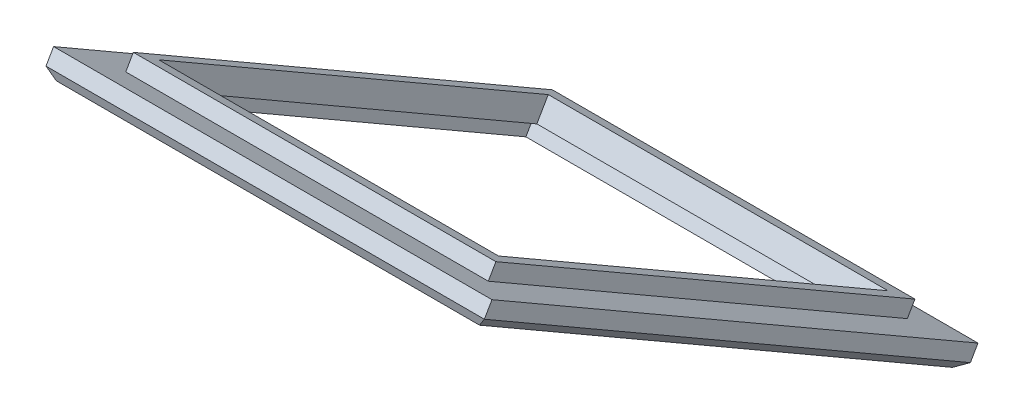
SolidWorks part; units mm, degrees
ref_plane "Front Plane" through (0, 0, 0) normal (1, 0, 0) x (0, 1, 0)
ref_plane "Top Plane" through (0, 0, 0) normal (0, 0, 1) x (0, 1, 0)
ref_plane "Right Plane" through (0, 0, 0) normal (0, 1, 0) x (-1, 0, 0)
sketch "Sketch1" plane through (0, -73.8743, 42.6513) normal (0, -0.866, 0.5) x (1, 0, 0)
  line L0 (-20.3754, 34.8073) -> (24.4246, 34.8073) construction
  line L1 (24.4246, 34.8073) -> (24.4246, 94.1073) construction
  line L2 (24.4246, 94.1073) -> (-20.3754, 94.1073) construction
  line L3 (-20.3754, 94.1073) -> (-20.3754, 34.8073) construction
  line L16 (-20.3754, 34.8073) -> (24.4246, 34.8073)
  line L17 (24.4246, 34.8073) -> (24.4246, 94.1073)
  line L18 (24.4246, 94.1073) -> (-20.3754, 94.1073)
  line L19 (-20.3754, 94.1073) -> (-20.3754, 34.8073)
  line L20 (-26.8754, 27.4573) -> (30.9246, 27.4573)
  line L21 (30.9246, 27.4573) -> (30.9246, 101.4573)
  line L22 (30.9246, 101.4573) -> (-26.8754, 101.4573)
  line L23 (-26.8754, 101.4573) -> (-26.8754, 27.4573)
  dimension "D1" = 6.5
  dimension "D2" = 7.35
  dimension "D3" = 7.35
  dimension "D4" = 6.5
extrude "Boss-Extrude1" add sketch "Sketch1" against normal blind 3
chamfer "Chamfer1" distance 1 angle 45 8 edges at (2.0246, -56.4706, 72.7953) (24.4246, -41.6456, 98.473) (2.0246, -26.8206, 124.1506) (-20.3754, -41.6456, 98.473) (2.0246, -60.1456, 66.4301) (30.9246, -41.6456, 98.473) (-26.8754, -41.6456, 98.473) (2.0246, -23.1456, 130.5159)
sketch "Sketch2" plane through (0, -71.2762, 41.1513) normal (0, 0.866, -0.5) x (-1, 0, 0)
  line L0 (20.3754, 94.1073) -> (20.3754, 34.8073) construction
  line L1 (-26.0246, 96.3573) -> (21.7754, 96.3573)
  line L2 (-26.0246, 96.3573) -> (-26.0246, 32.5573)
  line L3 (-26.0246, 32.5573) -> (21.7754, 32.5573)
  line L4 (21.7754, 96.3573) -> (21.7754, 32.5573)
  line L5 (20.3754, 34.8073) -> (-24.4246, 34.8073) construction
  line L6 (-24.4246, 34.8073) -> (-24.4246, 94.1073) construction
  line L7 (-24.4246, 94.1073) -> (20.3754, 94.1073) construction
  line L8 (20.3754, 94.1073) -> (20.3754, 34.8073)
  line L9 (20.3754, 34.8073) -> (-24.4246, 34.8073)
  line L10 (-24.4246, 34.8073) -> (-24.4246, 94.1073)
  line L11 (-24.4246, 94.1073) -> (20.3754, 94.1073)
  line L12 (-26.1246, 32.4573) -> (-26.1246, 96.4573) construction
  line L13 (21.8754, 96.4573) -> (21.8754, 32.4573) construction
  line L14 (-26.1246, 96.4573) -> (21.8754, 96.4573) construction
  line L15 (21.8754, 32.4573) -> (-26.1246, 32.4573) construction
  dimension "D1" = 0.1
  dimension "D2" = 0.1
  dimension "D3" = 0.1
  dimension "D4" = 0.1
extrude "Boss-Extrude2" add sketch "Sketch2" along normal up to surface (2 mm away)
sketch "Sketch4" plane through (0, -73.8743, 42.6513) normal (0, -0.866, 0.5) x (1, 0, 0)
  line L0 (-21.3754, 33.8073) -> (-21.3754, 95.1073) construction
  line L1 (-22.0754, 95.5573) -> (26.1246, 95.5573)
  line L2 (-22.0754, 95.5573) -> (-22.0754, 33.3573)
  line L3 (-22.0754, 33.3573) -> (26.1246, 33.3573)
  line L4 (26.1246, 95.5573) -> (26.1246, 33.3573)
  line L5 (-21.3754, 95.1073) -> (25.4246, 95.1073) construction
  point P6 (-21.3754, 64.4573)
  point P7 (-22.0754, 64.4573)
  point P10 (2.0246, 95.1073)
  point P11 (2.0246, 95.5573)
  dimension "D1" = 62.2
  dimension "D2" = 48.2
extrude "Cut-Extrude1" cut sketch "Sketch4" against normal blind 2
